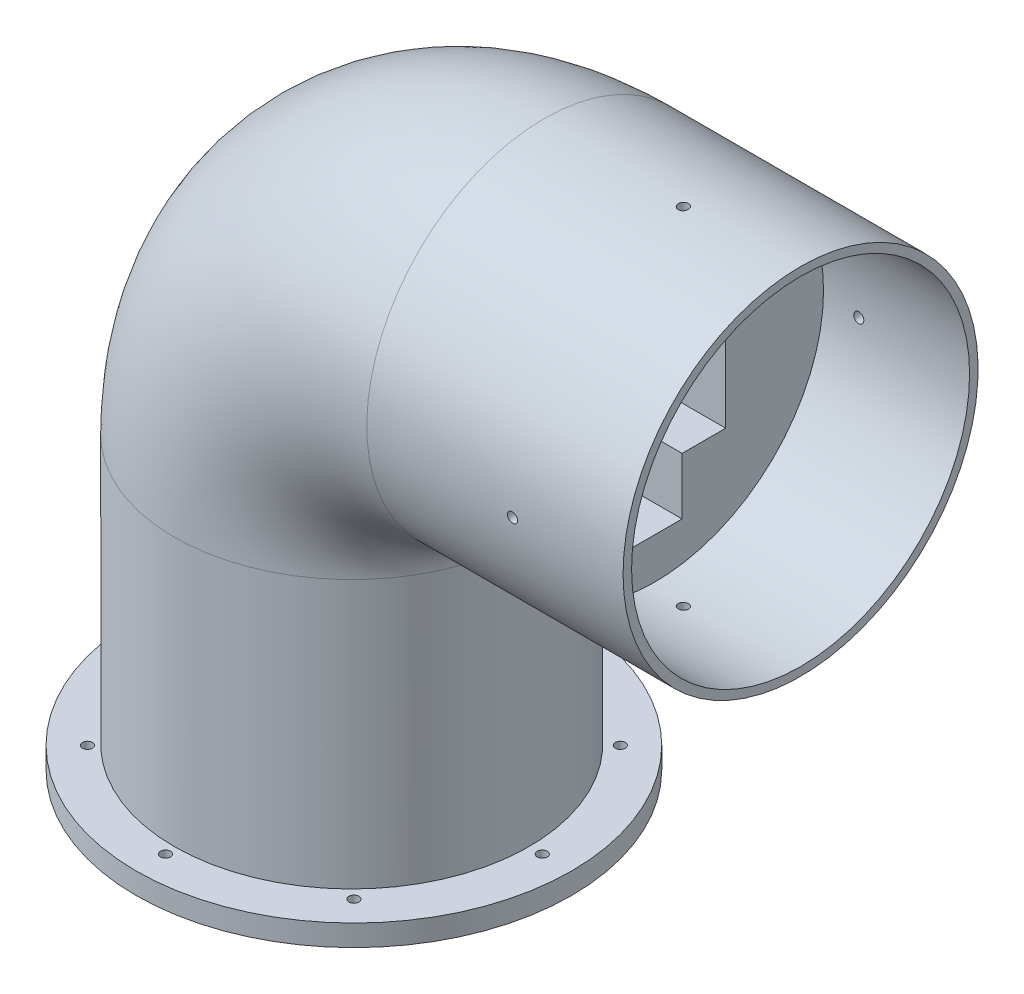
SolidWorks part; units mm, degrees
material "ABS"
ref_plane "Front Plane" through (0, 0, 0) normal (0, 0, 1) x (1, 0, 0)
ref_plane "Top Plane" through (0, 0, 0) normal (0, 1, 0) x (1, 0, 0)
ref_plane "Right Plane" through (0, 0, 0) normal (1, 0, 0) x (0, 0, -1)
sketch "Sketch4" plane through (0, 0, 0) normal (0, 0, 1) x (1, 0, 0)
  line L0 (-0.649, -43.2368) -> (-0.649, 36.7632)
  line L1 (56.851, 94.2632) -> (133.371, 94.2632)
  arc A0 (-0.649, 36.7632) -> (56.851, 94.2632) centre (56.851, 36.7632) cw
  point P5 (16.1924, 77.4218)
  dimension "D1" = 80
  dimension "D2" = 76.52
  dimension "D3" = 57.5
sweep "Sweep5" add path "Sketch4" circular profile diameter 106 parameters "D3"=106
shell "Shell13" thickness 2.54
sketch "Sketch19" plane through (0, -43.2368, 0) normal (0, -1, 0) x (1, 0, 0)
  circle A0 centre (0, 0) radius 65
  dimension "D1" = 130
extrude "Boss-Extrude1" add sketch "Sketch19" along normal blind 6.35
sketch "Sketch20" plane through (0, -49.5868, 0) normal (0, -1, 0) x (-1, 0, 0)
  circle A0 centre (0, 0) radius 38.1
  dimension "D1" = 76.2
extrude "Cut-Extrude1" cut sketch "Sketch20" against normal blind 6.35
ref_plane "Plane1" through (80, 0, 0) normal (1, 0, 0) x (0, 0, -1)
sketch "Sketch24" plane through (80, 0, 0) normal (1, 0, 0) x (0, 0, -1)
  line L0 (-8, 73.2632) -> (-8, 56.3008)
  line L1 (-21, 73.2632) -> (-8, 73.2632)
  line L2 (-21, 73.2632) -> (-21, 115.2632)
  line L3 (-21, 115.2632) -> (21, 115.2632)
  line L4 (21, 73.2632) -> (21, 115.2632)
  line L5 (-21, 73.2632) -> (21, 115.2632) construction
  line L6 (-21, 115.2632) -> (21, 73.2632) construction
  line L9 (-8, 56.3008) -> (8, 56.3008)
  line L11 (0, 73.2632) -> (8, 56.3008) construction
  line L12 (-8, 56.3008) -> (0, 73.2632) construction
  line L13 (8, 73.2632) -> (8, 56.3008)
  line L14 (8, 73.2632) -> (21, 73.2632)
  circle A0 centre (0, 94.2632) radius 50.225
  point P3 (0, 73.2632)
  dimension "D4" = 100.45
  dimension "D1" = 42
  dimension "D2" = 42
  dimension "D3" = 16
extrude "Boss-Extrude2" add sketch "Sketch24" against normal blind 5 and the other way blind 10
sketch "Sketch32" plane through (0, 0, 0) normal (0, 0, 1) x (1, 0, 0)
  circle A0 centre (100.3231, 92.3008) radius 1.5
  dimension "D1" = 3
extrude "Cut-Extrude3" cut sketch "Sketch32" against normal through all and the other way through all
pattern_circular "CirPattern1" count 2 every 90 about axis through (133.371, 94.2632, 0) along (-1, 0, 0) of "Cut-Extrude3"
sketch "Sketch49" plane through (0, -49.5868, 0) normal (0, -1, 0) x (1, 0, 0)
  circle A1 centre (0, 56.25) radius 1.5
extrude "Cut-Extrude4" cut sketch "Sketch49" against normal blind 10
pattern_circular "CirPattern2" count 8 over 360 about axis through (0, 0, 0) along (0, 1, 0) of "Cut-Extrude4"
